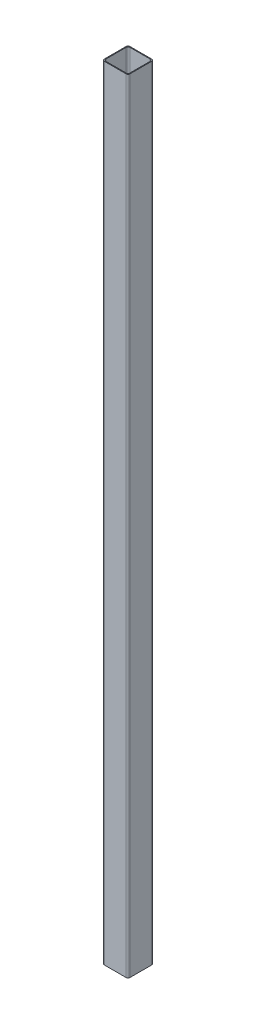
SolidWorks part; units mm, degrees
ref_plane "Plano frontal" through (0, 0, 0) normal (0, 0, 1) x (1, 0, 0)
ref_plane "Plano superior" through (0, 0, 0) normal (0, 1, 0) x (1, 0, 0)
ref_plane "Plano direito" through (0, 0, 0) normal (1, 0, 0) x (0, 0, -1)
sketch "Esboço1" plane through (0, 0, 0) normal (0, 1, 0) x (1, 0, 0)
  line L0 (-18.8, -18.8) -> (-18.8, 18.8)
  line L1 (20, -20) -> (-20, -20)
  line L2 (20, -20) -> (20, 20)
  line L3 (20, 20) -> (-20, 20)
  line L4 (-20, -20) -> (-20, 20)
  line L5 (20, -20) -> (-20, 20) construction
  line L6 (20, 20) -> (-20, -20) construction
  line L7 (18.8, 18.8) -> (-18.8, 18.8)
  line L8 (18.8, -18.8) -> (18.8, 18.8)
  line L9 (18.8, -18.8) -> (-18.8, -18.8)
  point P0 (0, 0)
  dimension "D1" = 40
  dimension "D2" = 40
  dimension "D3" = 1.2
extrude "Ressalto-extrusão1" add sketch "Esboço1" along normal mid plane 1220
fillet "Filete1" radius 3 8 edges at (-20, 0, -20) (20, 0, -20) (18.8, 0, -18.8) (18.8, 0, 18.8) (-18.8, 0, 18.8) (-18.8, 0, -18.8) (-20, 0, 20) (20, 0, 20)
